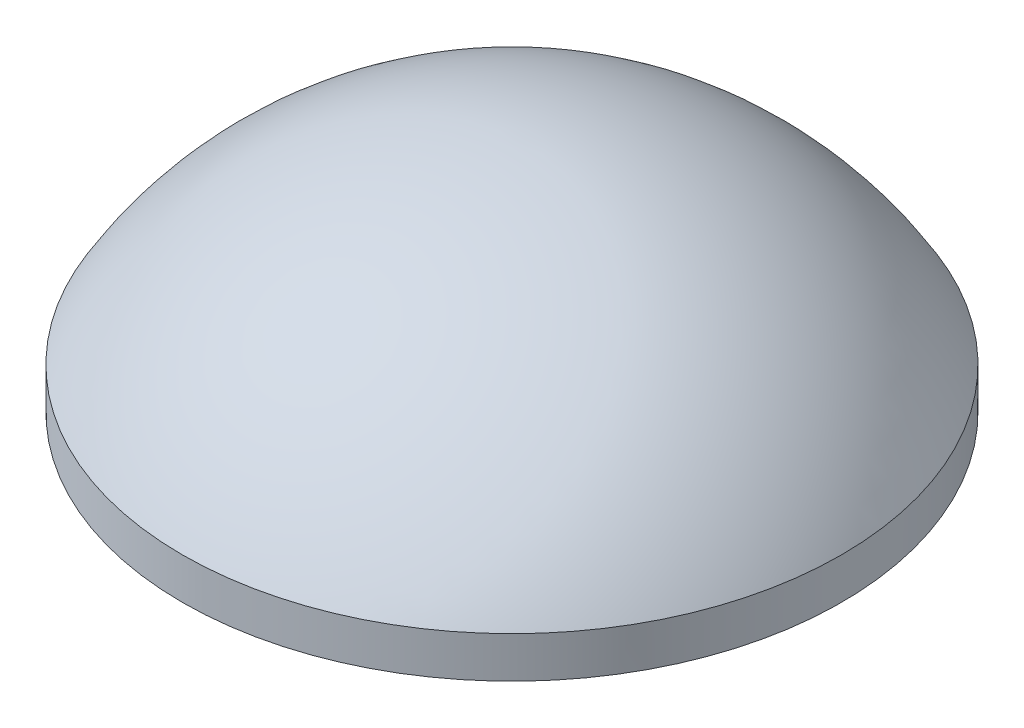
SolidWorks part; units mm, degrees
material "Benutzerdefinierter Kunststoff"
ref_plane "Ebene vorne" through (0, 0, 0) normal (0, 0, 1) x (1, 0, 0)
ref_plane "Ebene oben" through (0, 0, 0) normal (0, 1, 0) x (1, 0, 0)
ref_plane "Ebene rechts" through (0, 0, 0) normal (1, 0, 0) x (0, 0, -1)
sketch "Skizze1" plane through (0, 0, 0) normal (0, 0, 1) x (1, 0, 0)
  line L0 (0, 66.7244) -> (0, -53.8987) construction
  line L1 (-4, 0) -> (0, 0)
  line L2 (-4, 0.5) -> (-4, 0)
  line L3 (0, 2.8) -> (-4.0249, 2.8) construction
  line L5 (0, 0) -> (0, 2.8)
  arc A0 (0, 2.8) -> (-4, 0.5) centre (0, -1.8283) ccw
  dimension "D1" = 8
  dimension "D2" = 0.5
  dimension "D3" = 2.8
revolve "Rotation1" add sketch "Skizze1" angle 360 about L0
